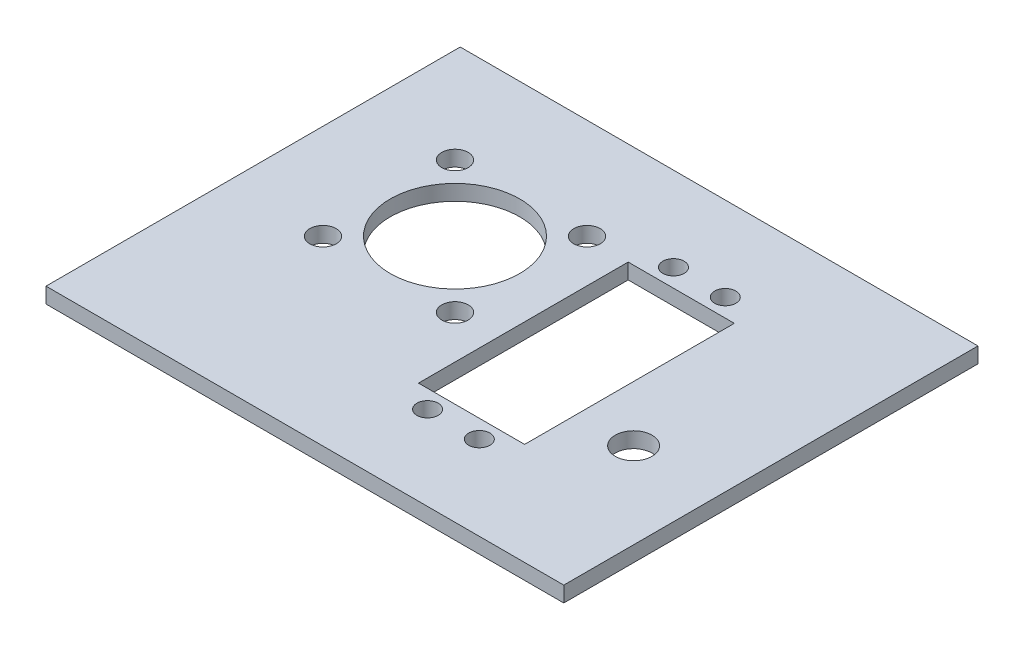
SolidWorks part; units mm, degrees
ref_plane "Płaszczyzna przednia" through (0, 0, 0) normal (0, 0, 1) x (1, 0, 0)
ref_plane "Płaszczyzna górna" through (0, 0, 0) normal (0, 1, 0) x (1, 0, 0)
ref_plane "Płaszczyzna prawa" through (0, 0, 0) normal (1, 0, 0) x (0, 0, -1)
sketch "Szkic1" plane through (0, 0, 0) normal (0, 1, 0) x (1, 0, 0)
  line L6 (-20.2688, 11.7569) -> (5.2312, -13.7431) construction
  line L11 (-38.6633, 31.161) -> (61.3367, 31.161)
  line L12 (-38.6633, 31.161) -> (-38.6633, -48.839)
  line L13 (-38.6633, -48.839) -> (61.3367, -48.839)
  line L14 (61.3367, 31.161) -> (61.3367, -48.839)
  line L15 (-20.2688, -13.7431) -> (5.2312, 11.7569) construction
  line L17 (13.5251, 11.411) -> (34.0251, 11.411)
  line L18 (13.5251, 11.411) -> (13.5251, -29.089)
  line L23 (13.5251, -29.089) -> (34.0251, -29.089)
  line L24 (34.0251, 11.411) -> (34.0251, -29.089)
  circle A0 centre (-7.5188, -0.9931) radius 12.5
  circle A2 centre (-20.2688, 11.7569) radius 2.55
  circle A3 centre (5.2312, 11.7569) radius 2.55
  circle A4 centre (5.2312, -13.7431) radius 2.55
  circle A5 centre (-20.2688, -13.7431) radius 2.55
  circle A6 centre (18.7751, 14.911) radius 2.05
  circle A7 centre (28.7751, 14.911) radius 2.05
  circle A8 centre (18.7751, -32.589) radius 2.05
  circle A9 centre (28.7751, -32.589) radius 2.05
  circle A10 centre (23.7751, -18.789) radius 0.5
  circle A11 centre (-7.5188, -0.9931) radius 0.5
  circle A12 centre (44.7751, -18.789) radius 3.55
  circle A13 centre (44.7751, -18.789) radius 0.5
  point P18 (23.7751, -29.089)
  point P22 (23.7751, 11.411)
  dimension "D3" = 10.3
  dimension "D5" = 3.5
  dimension "D13" = 36
  dimension "D18" = 19.75
  dimension "D20" = 5.1
  dimension "D22" = 25
  dimension "D23" = 7.1
  dimension "D24" = 4.1
  dimension "D25" = 47.5
  dimension "D1" = 100
  dimension "D2" = 80
  dimension "D4" = 10.25
  dimension "D6" = 3.5
  dimension "D7" = 5
  dimension "D8" = 5
  dimension "D9" = 3.5
  dimension "D10" = 3.5
  dimension "D11" = 5
  dimension "D12" = 5
  dimension "D14" = 21
  dimension "D15" = 40.5
  dimension "D16" = 20.5
  dimension "D17" = 10.3
  dimension "D19" = 19.75
  dimension "D21" = 25.5
extrude "Dodanie-wyciągnięcie1" add sketch "Szkic1" along normal blind 3 contours L14 L11 L12 L13 A12 A9 A8 A7 A6 A5 A4 A3 A2 A0 L17 L24 L23 L18
